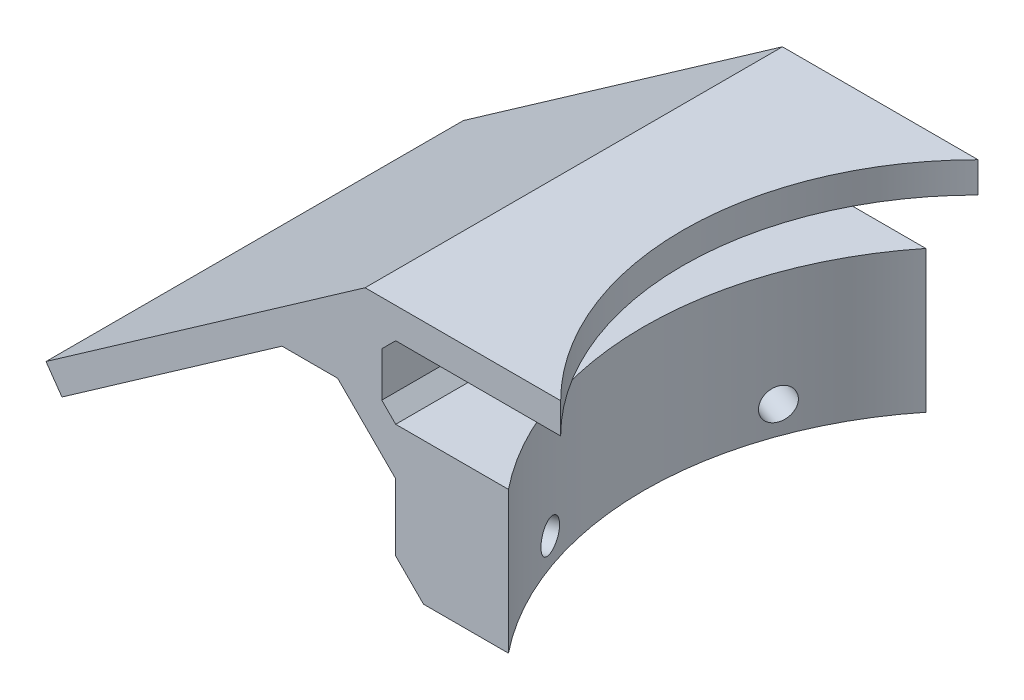
SolidWorks part; units mm, degrees
ref_plane "Piano frontale" through (0, 0, 0) normal (0, 0, 1) x (1, 0, 0)
ref_plane "Piano superiore" through (0, 0, 0) normal (0, 1, 0) x (1, 0, 0)
ref_plane "Piano destro" through (0, 0, 0) normal (1, 0, 0) x (0, 0, -1)
sketch "Schizzo1" plane through (0, 0, 0) normal (0, 0, 1) x (1, 0, 0)
  line L16 (-6, 38.5) -> (38.5, 38.5)
  line L17 (38.5, 38.5) -> (38.5, 44)
  line L18 (38.5, 44) -> (-11.5, 44)
  line L19 (-11.5, 44) -> (-68.8406, 3.8496)
  line L20 (-68.8406, 3.8496) -> (-65.9728, -0.2461)
  line L21 (-65.9728, -0.2461) -> (-26.4284, 27.4431)
  line L23 (-16.4284, 27.4431) -> (-6, 17.0147)
  line L24 (-6, 17.0147) -> (-6, 5)
  line L25 (-1, 0) -> (0, 0)
  line L28 (0, 0) -> (20.5, 0)
  line L29 (20.5, 0) -> (20.5, 25.5)
  line L30 (20.5, 25.5) -> (0, 25.5)
  line L31 (0, 0) -> (0, 25.5) construction
  line L32 (0, 25.5) -> (-6, 25.5)
  line L33 (-6, 25.5) -> (-8.5, 28)
  line L34 (-6, 5) -> (-1, 0)
  line L35 (-6, 17.0147) -> (-6, 25.5) construction
  line L36 (-8.5, 36) -> (-6, 38.5)
  line L37 (-6, 38.5) -> (-6, 25.5) construction
  line L38 (-8.5, 28) -> (-8.5, 36)
  line L39 (-16.4284, 27.4431) -> (-26.4284, 27.4431)
  dimension "D2" = 6
  dimension "D3" = 25.5
  dimension "D4" = 20.5
  dimension "D5" = 6
  dimension "D6" = 35
  dimension "D7" = 45
  dimension "D8" = 5
  dimension "D9" = 13
  dimension "D10" = 5.5
  dimension "D11" = 5
  dimension "D12" = 70
  dimension "D13" = 38.5
  dimension "D14" = 45
  dimension "D15" = 29
  dimension "D16" = 50
  dimension "D17" = 10
extrude "Estrusione-Estrusione1" add sketch "Schizzo1" along normal blind 75
sketch "Schizzo2" plane through (0, 44, 0) normal (0, 1, 0) x (1, 0, 0)
  line L0 (8.1, -75) -> (8.1, 0) construction
  line L1 (38.5, -75) -> (-11.5, -75) construction
  line L2 (38.5, 0) -> (-11.5, 0) construction
  line L3 (8.1, -37.5) -> (61.1, -37.5) construction
  line L6 (38.5, -75) -> (38.5, 0) construction
  circle A1 centre (61.1, -37.5) radius 53
  dimension "D1" = 30.4
  dimension "D3" = 106
extrude "Taglio-Estrusione1" cut sketch "Schizzo2" against normal blind 75
sketch "Schizzo3" plane through (0, 0, 0) normal (0, -1, 0) x (1, 0, 0)
  line L4 (-1, 37.5) -> (61.1, 37.5) construction
  line L6 (-1, 75) -> (-1, 0) construction
  line L7 (-6, 75) -> (-6, 0) construction
  circle A1 centre (61.1, 37.5) radius 60
  point P3 (-1, 37.5)
  dimension "D1" = 67.1
  dimension "D2" = 120
extrude "Taglio-Estrusione2" cut sketch "Schizzo3" against normal blind 28
hole_wizard "Foro per Vite M3-1" positions "Schizzo3D1" profile "Schizzo4" hole size "M3" standard "ISO"
sketch3d "Schizzo3D1"
  line L0 (4.7184, 5, 58.0212) -> (4.7184, 5, 16.9788) construction
  line L2 (4.7184, 5, 37.5) -> (61.1, 5, 37.5) construction
  line L3 (61.1, 5, 37.5) -> (4.7184, 5, 58.0212) construction
  line L5 (61.1, 5, 37.5) -> (4.7184, 5, 16.9788) construction
  point P0 (4.7184, 5, 16.9788)
  point P2 (4.7184, 5, 58.0212)
  dimension "D1" = 5
  dimension "D2" = 60
  dimension "D3" = 20
  dimension "D4" = 20
sketch "Schizzo4" plane through (4.7184, 5, 16.9788) normal (0, 1, 0) x (0.342, 0, -0.9397)
  line L0 (0, 0) -> (0, 9.7824)
  line L1 (0, 9.7824) -> (2.8, 8.1)
  line L2 (2.8, 8.1) -> (2.8, 0)
  line L5 (2.8, 0) -> (0, 0)
  line L10 (0, 9.7824) -> (-2.8, 8.1) construction
  line L11 (0, -6.35) -> (0, 107.95) construction
  dimension "Hole Dia." = 5.6
  dimension "Hole Depth" = 8.1
  dimension "Drill Angle" = 118
